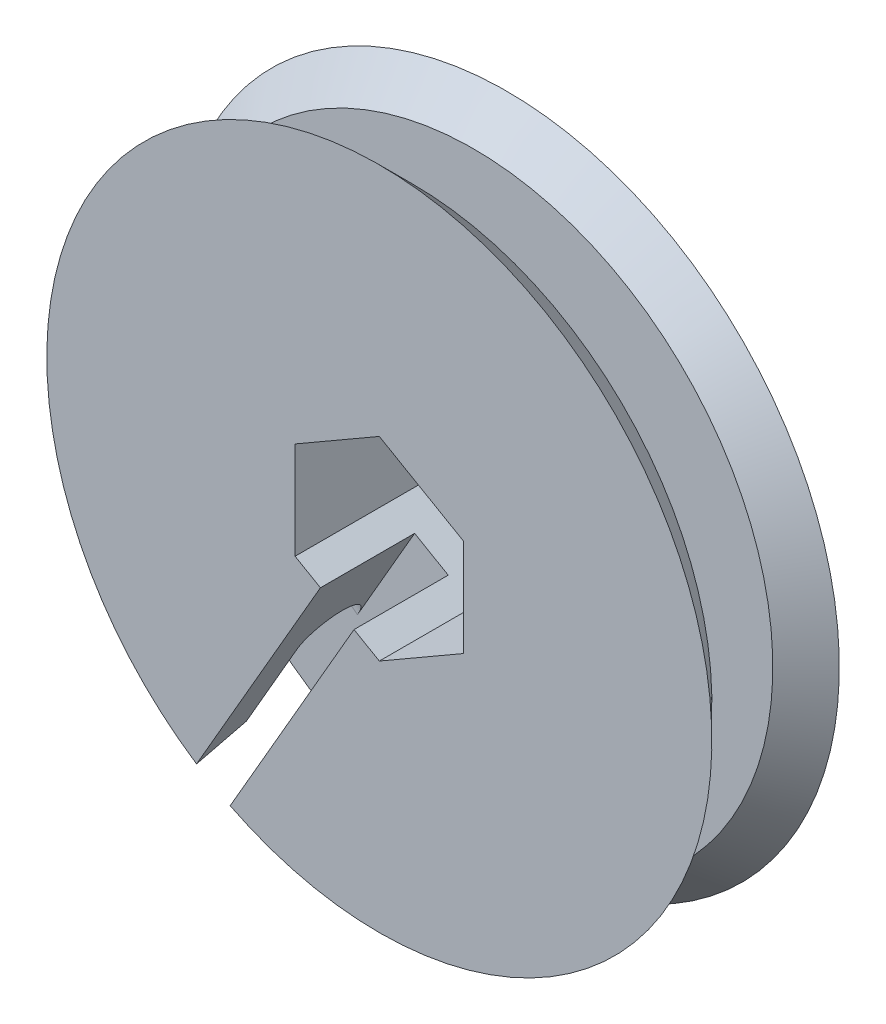
SolidWorks part; units mm, degrees
ref_plane "Plan de face" through (0, 0, 0) normal (1, 0, 0) x (0, 1, 0)
ref_plane "Plan de dessus" through (0, 0, 0) normal (0, 0, 1) x (0, 1, 0)
ref_plane "Plan de droite" through (0, 0, 0) normal (0, 1, 0) x (-1, 0, 0)
sketch "Esquisse1" plane through (0, 0, 0) normal (0, 1, 0) x (-1, 0, 0)
  line L0 (0, 0) -> (0, 70.4084) construction
  line L1 (0, 0) -> (30, 0)
  line L2 (30, 0) -> (27, 3)
  line L3 (27, 3) -> (18, 3)
  line L4 (18, 3) -> (18, 8.5)
  line L5 (18, 8.5) -> (27, 8.5)
  line L6 (27, 8.5) -> (30, 11.5)
  line L7 (30, 11.5) -> (0, 11.5)
  line L8 (0, 11.5) -> (0, 0)
  circle A0 centre (18, 5.75) radius 2.75
  point P3 (18, 5.75)
  point P11 (0, 5.75)
  dimension "D1" = 5.5
  dimension "D2" = 30
  dimension "D3" = 3
  dimension "D4" = 18
  dimension "D5" = 3
revolve "Révolution1" add sketch "Esquisse1" angle 360 about L0
sketch "Esquisse2" plane through (0, 0, 0) normal (0, 0, -1) x (1, 0, 0)
  line L1 (7.6, 4.3879) -> (0, 8.7757)
  line L2 (0, 8.7757) -> (-7.6, 4.3879)
  line L3 (-7.6, 4.3879) -> (-7.6, -4.3879)
  line L4 (-7.6, -4.3879) -> (0, -8.7757)
  line L5 (0, -8.7757) -> (7.6, -4.3879)
  line L6 (7.6, -4.3879) -> (7.6, 4.3879)
  circle A0 centre (0, 0) radius 7.6 construction
  dimension "D1" = 15.2
extrude "Enlèv. mat.-Extru.1" cut sketch "Esquisse2" against normal through all
sketch "Esquisse3" plane through (0, 0, 11.5) normal (0, 0, 1) x (1, 0, 0)
  line L1 (-14.7845, -29.1074) -> (-17.8155, -27.3574)
  line L2 (-14.7845, -29.1074) -> (-2.2845, -7.4568)
  line L3 (-2.2845, -7.4568) -> (-5.3155, -5.7068)
  line L4 (-17.8155, -27.3574) -> (-5.3155, -5.7068)
  line L5 (-14.7845, -29.1074) -> (-5.3155, -5.7068) construction
  line L6 (-2.2845, -7.4568) -> (-17.8155, -27.3574) construction
  line L7 (-7.5, -4.3301) -> (0, -8.6603) construction
  line L9 (0, -8.7757) -> (-7.6, -4.3879) construction
  point P0 (-3.8, -6.5818)
  point P11 (-3.8, -6.5818)
  dimension "D1" = 3.5
  dimension "D2" = 25
extrude "Enlèv. mat.-Extru.2" cut sketch "Esquisse3" against normal up to surface (8.5 mm away) up to face at (-18, 0, 3)
